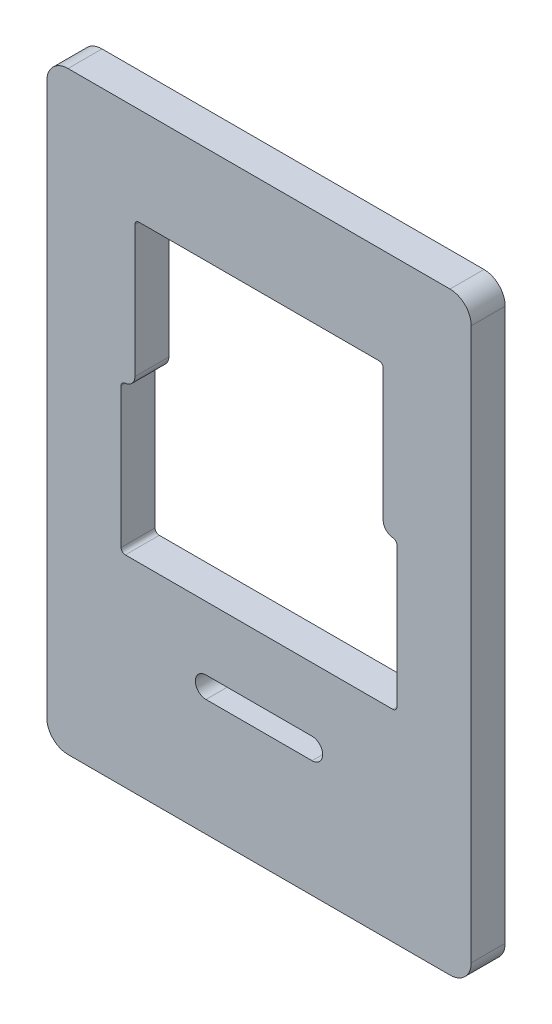
SolidWorks part; units mm, degrees
material "Silicon Rubber"
ref_plane "Front Plane" through (0, 0, 0) normal (0, 0, 1) x (1, 0, 0)
ref_plane "Top Plane" through (0, 0, 0) normal (0, 1, 0) x (1, 0, 0)
ref_plane "Right Plane" through (0, 0, 0) normal (1, 0, 0) x (0, 0, -1)
sketch "MainBodyS" plane through (0, 0, 0) normal (0, 0, 1) x (1, 0, 0)
  line L1 (-10, 14) -> (10, 14)
  line L2 (-10, 14) -> (-10, -14)
  line L3 (-10, -14) -> (10, -14)
  line L4 (10, 14) -> (10, -14)
  line L5 (-10, 14) -> (10, -14) construction
  line L6 (-10, -14) -> (10, 14) construction
  point P0 (0, 0)
  dimension "D1" = 20
  dimension "D2" = 28
extrude "MAIN BODY" add sketch "MainBodyS" against normal blind 1.6
sketch "GroundCutS" plane through (0, 0, 0) normal (0, 0, 1) x (1, 0, 0)
  line L0 (-2.5, -8) -> (2.5, -8) construction
  line L1 (-2.5, -7.5) -> (2.5, -7.5)
  line L2 (-2.5, -8.5) -> (2.5, -8.5)
  line L3 (0, -14) -> (0, -8) construction
  line L4 (-10, -14) -> (10, -14) construction
  arc A0 (-2.5, -7.5) -> (-2.5, -8.5) centre (-2.5, -8) ccw
  arc A1 (2.5, -8.5) -> (2.5, -7.5) centre (2.5, -8) ccw
  point P2 (0, -8)
  dimension "D1" = 1
  dimension "D2" = 5
  dimension "D3" = 6
extrude "GROUND CUT" cut sketch "GroundCutS" against normal through all
sketch "MidCutS" plane through (0, 0, 0) normal (0, 0, 1) x (1, 0, 0)
  line L0 (0, 0) -> (0, -1) construction
  line L1 (-6.5, 2.5) -> (6.5, 2.5)
  line L2 (-6.5, 2.5) -> (-6.5, -4.5)
  line L3 (-6.5, -4.5) -> (6.5, -4.5)
  line L4 (6.5, 2.5) -> (6.5, -4.5)
  line L5 (-6.5, 2.5) -> (6.5, -4.5) construction
  line L6 (-6.5, -4.5) -> (6.5, 2.5) construction
  line L7 (-10, 14) -> (-10, -14) construction
  arc A0 (-2.5, -7.5) -> (-2.5, -8.5) centre (-2.5, -8) ccw construction
  point P0 (0, -1)
  dimension "D4" = 3.5
  dimension "D1" = 3.5
  dimension "D2" = 7
  dimension "D3" = 13
extrude "MID CUT" cut sketch "MidCutS" against normal through all
sketch "TopPowerAccessCutS" plane through (0, 0, 0) normal (0, 0, 1) x (1, 0, 0)
  line L0 (6.5, 2.5) -> (-6.5, 2.5) construction
  line L1 (-5.85, 9.4) -> (5.85, 9.4)
  line L2 (-5.85, 9.4) -> (-5.85, 2.5)
  line L3 (-5.85, 2.5) -> (5.85, 2.5)
  line L4 (5.85, 9.4) -> (5.85, 2.5)
  line L5 (-5.85, 9.4) -> (5.85, 2.5) construction
  line L6 (-5.85, 2.5) -> (5.85, 9.4) construction
  line L8 (-6.5, 2.5) -> (-6.5, -4.5) construction
  line L10 (0, 0) -> (0, 5.95) construction
  line L11 (10, 14) -> (-10, 14) construction
  point P0 (0, 5.95)
  dimension "D1" = 0.65
  dimension "D2" = 4.6
extrude "TOP POWER ACCESS CUT" cut sketch "TopPowerAccessCutS" against normal through all
fillet "MC FILLET" radius 0.5 2 edges at (5.85, 2.5, -0.8) (-5.85, 2.5, -0.8)
fillet "ALL INNER CUTS FILLETS" radius 0.2 6 edges at (-6.5, -4.5, -0.8) (6.5, -4.5, -0.8) (6.5, 2.5, -0.8) (-6.5, 2.5, -0.8) (-5.85, 9.4, -0.8) (5.85, 9.4, -0.8)
fillet "OUTER FILLETS" radius 1 4 edges at (-10, -14, -0.8) (10, -14, -0.8) (10, 14, -0.8) (-10, 14, -0.8)
